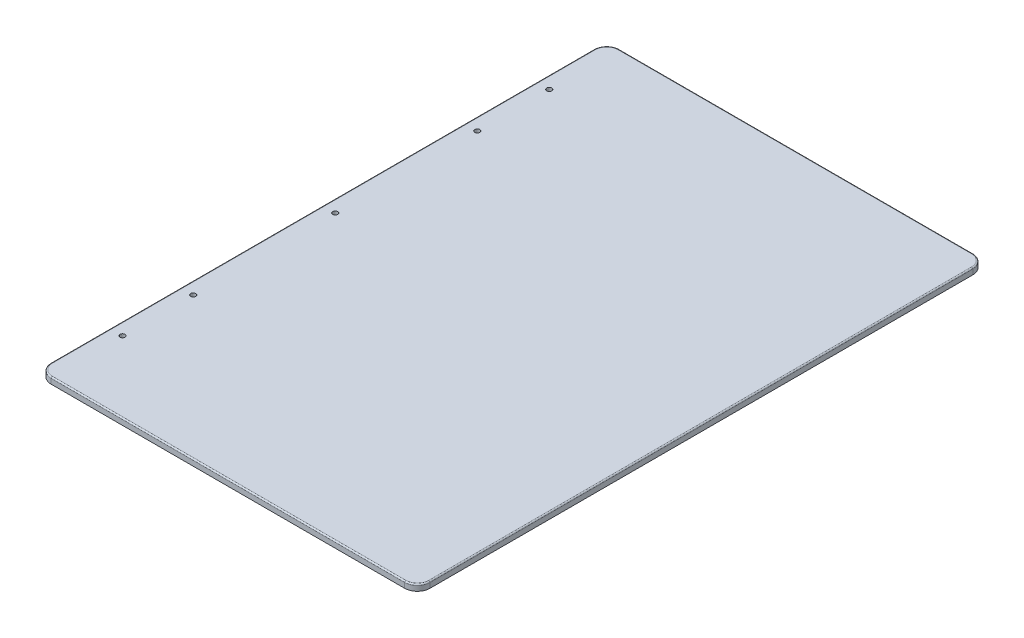
SolidWorks part; units mm, degrees
ref_plane "Front Plane" through (0, 0, 0) normal (0, 0, 1) x (1, 0, 0)
ref_plane "Top Plane" through (0, 0, 0) normal (0, 1, 0) x (1, 0, 0)
ref_plane "Right Plane" through (0, 0, 0) normal (1, 0, 0) x (0, 0, -1)
sketch "Sketch1" plane through (0, 0, 0) normal (0, 1, 0) x (1, 0, 0)
  line L1 (-150, -225) -> (150, -225)
  line L2 (-150, -225) -> (-150, 225)
  line L3 (-150, 225) -> (150, 225)
  line L4 (150, -225) -> (150, 225)
  line L5 (-150, -225) -> (150, 225) construction
  line L6 (-150, 225) -> (150, -225) construction
  point P0 (0, 0)
  dimension "D1" = 300
  dimension "D2" = 450
extrude "Boss-Extrude1" add sketch "Sketch1" along normal blind 5
sketch "Sketch2" plane through (0, 5, 0) normal (0, 1, 0) x (1, 0, 0)
  line L0 (-140, 225) -> (-140, -225) construction
  line L1 (150, 225) -> (-150, 225) construction
  line L2 (-150, -225) -> (150, -225) construction
  line L3 (-150, 225) -> (-150, -225) construction
  circle A0 centre (-140, 0) radius 2
  circle A1 centre (-140, 112.5) radius 2
  circle A2 centre (-140, -112.5) radius 2
  circle A3 centre (-140, 169.5) radius 2
  circle A4 centre (-140, -168.5) radius 2
  point P12 (0, 0)
  dimension "D2" = 112.5
  dimension "D5" = 56
  dimension "D6" = 4
  dimension "D7" = 4
  dimension "D8" = 4
  dimension "D9" = 4
  dimension "D10" = 4
  dimension "D1" = 10
  dimension "D3" = 112.5
  dimension "D4" = 57
extrude "Cut-Extrude1" cut sketch "Sketch2" against normal through all
fillet "Fillet2" radius 10 4 edges at (-150, 2.5, -225) (150, 2.5, -225) (150, 2.5, 225) (-150, 2.5, 225)
fillet "Fillet1" radius 1 8 edges at (147.0711, 5, 222.0711) (0, 5, 225) (-147.0711, 5, 222.0711) (-150, 5, 0) (-147.0711, 5, -222.0711) (0, 5, -225) (147.0711, 5, -222.0711) (150, 5, 0)
sketch "Sketch4" plane through (0, 0, 0) normal (0, -1, 0) x (1, 0, 0)
  line L0 (-150, 205) -> (150, 205) construction
  line L1 (-150, -215) -> (-150, 215) construction
  line L2 (150, 215) -> (150, -215) construction
  line L3 (-150, -205) -> (150, -205) construction
  line L4 (-140, 225) -> (140, 225) construction
  line L5 (140, -225) -> (-140, -225) construction
  line L6 (15, -205) -> (15, 205)
  line L7 (-5, -205) -> (5, -205)
  line L8 (-5, -205) -> (-5, 205)
  line L9 (-5, 205) -> (5, 205)
  line L10 (5, -205) -> (5, 205)
  line L11 (-5, -205) -> (5, 205) construction
  line L12 (-5, 205) -> (5, -205) construction
  line L13 (15, -205) -> (25, -205)
  line L14 (25, -205) -> (25, 205)
  line L15 (15, 205) -> (25, 205)
  line L16 (35, -205) -> (35, 205)
  line L17 (35, -205) -> (45, -205)
  line L18 (45, -205) -> (45, 205)
  line L19 (35, 205) -> (45, 205)
  line L20 (55, -205) -> (55, 205)
  line L21 (55, -205) -> (65, -205)
  line L22 (65, -205) -> (65, 205)
  line L23 (55, 205) -> (65, 205)
  line L24 (75, -205) -> (75, 205)
  line L25 (75, -205) -> (85, -205)
  line L26 (85, -205) -> (85, 205)
  line L27 (75, 205) -> (85, 205)
  line L28 (95, -205) -> (95, 205)
  line L29 (95, -205) -> (105, -205)
  line L30 (105, -205) -> (105, 205)
  line L31 (95, 205) -> (105, 205)
  line L32 (-25, -205) -> (-25, 205)
  line L33 (-25, -205) -> (-15, -205)
  line L34 (-15, -205) -> (-15, 205)
  line L35 (-25, 205) -> (-15, 205)
  line L36 (-45, -205) -> (-45, 205)
  line L37 (-45, -205) -> (-35, -205)
  line L38 (-35, -205) -> (-35, 205)
  line L39 (-45, 205) -> (-35, 205)
  line L40 (-65, -205) -> (-65, 205)
  line L41 (-65, -205) -> (-55, -205)
  line L42 (-55, -205) -> (-55, 205)
  line L43 (-65, 205) -> (-55, 205)
  line L44 (-85, -205) -> (-85, 205)
  line L45 (-85, -205) -> (-75, -205)
  line L46 (-75, -205) -> (-75, 205)
  line L47 (-85, 205) -> (-75, 205)
  line L48 (-105, -205) -> (-105, 205)
  line L49 (-105, -205) -> (-95, -205)
  line L50 (-95, -205) -> (-95, 205)
  line L51 (-105, 205) -> (-95, 205)
  point P12 (0, 0)
  dimension "D1" = 20
  dimension "D2" = 20
  dimension "D3" = 10
  dimension "D4" = 6
  dimension "D5" = 6
extrude "Cut-Extrude3" cut sketch "Sketch4" against normal blind 0.5
